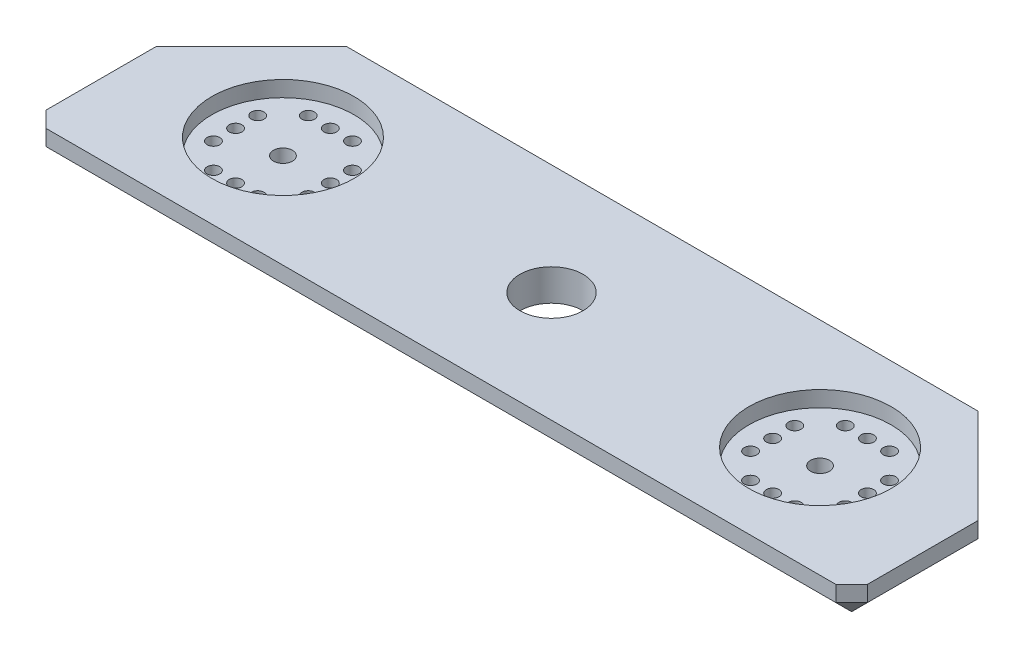
SolidWorks part; units mm, degrees
ref_plane "前视基准面" through (0, 0, 0) normal (0, 0, 1) x (1, 0, 0)
ref_plane "上视基准面" through (0, 0, 0) normal (0, 1, 0) x (1, 0, 0)
ref_plane "右视基准面" through (0, 0, 0) normal (1, 0, 0) x (0, 0, -1)
other "Configuration Table"
sketch "Sketch1" plane through (0, 0, 0) normal (0, 1, 0) x (1, 0, 0)
  line L15 (-65, -17.5) -> (-65, 2.5)
  line L16 (-65, -17.5) -> (65, -17.5)
  line L17 (-65, -17.5) -> (-65, 17.5)
  line L18 (-65, 17.5) -> (65, 17.5)
  line L19 (65, -17.5) -> (65, 17.5)
  line L20 (-65, -17.5) -> (65, 17.5) construction
  line L21 (-65, 17.5) -> (65, -17.5) construction
  line L22 (-65, 2.5) -> (-50, 17.5)
  line L23 (0, 0) -> (0, 17.5) construction
  line L24 (65, 2.5) -> (50, 17.5)
  point P0 (0, 0)
  dimension "D2" = 35
  dimension "D4" = 15
  dimension "D1" = 130
  dimension "D3" = 20
extrude "Boss-Extrude1" add sketch "Sketch1" along normal blind 5
sketch "Sketch2" plane through (0, 5, 0) normal (0, 1, 0) x (1, 0, 0)
  line L0 (0, 0) -> (-42.5, 0) construction
  line L1 (0, 0) -> (0, -17.5) construction
  line L2 (-65, -17.5) -> (65, -17.5) construction
  circle A0 centre (-42.5, 0) radius 11.25
  circle A1 centre (42.5, 0) radius 11.25
  dimension "D1" = 22.5
  dimension "D2" = 42.5
extrude "Cut-Extrude1" cut sketch "Sketch2" against normal blind 2.5
sketch "Sketch3" plane through (0, 5, 0) normal (0, 1, 0) x (1, 0, 0)
  line L0 (0, 0) -> (42.5, 0) construction
  line L1 (42.5, 7.5) -> (46, 7.5) construction
  line L2 (42.5, 7.5) -> (42.5, 13.9618) construction
  line L3 (0, 0) -> (0, 17.5) construction
  line L4 (-50, 17.5) -> (50, 17.5) construction
  line L5 (-42.5, 7.5) -> (-42.5, 13.9618) construction
  line L6 (-42.5, 7.5) -> (-46, 7.5) construction
  circle A0 centre (42.5, 0) radius 1.5
  circle A1 centre (42.5, 0) radius 7.5 construction
  circle A2 centre (42.5, 7.5) radius 1
  circle A3 centre (46, 7.5) radius 1
  circle A4 centre (39, 7.5) radius 1
  circle A5 centre (50, 3.5) radius 1
  circle A6 centre (50, 0) radius 1
  circle A7 centre (50, -3.5) radius 1
  circle A8 centre (46, -7.5) radius 1
  circle A9 centre (42.5, -7.5) radius 1
  circle A10 centre (39, -7.5) radius 1
  circle A11 centre (35, -3.5) radius 1
  circle A12 centre (35, 0) radius 1
  circle A13 centre (35, 3.5) radius 1
  circle A14 centre (-42.5, 0) radius 7.5 construction
  circle A15 centre (-35, 3.5) radius 1
  circle A16 centre (-35, 0) radius 1
  circle A17 centre (-35, -3.5) radius 1
  circle A18 centre (-39, -7.5) radius 1
  circle A19 centre (-42.5, -7.5) radius 1
  circle A20 centre (-46, -7.5) radius 1
  circle A21 centre (-50, -3.5) radius 1
  circle A22 centre (-50, 0) radius 1
  circle A23 centre (-50, 3.5) radius 1
  circle A24 centre (-39, 7.5) radius 1
  circle A25 centre (-46, 7.5) radius 1
  circle A26 centre (-42.5, 7.5) radius 1
  circle A27 centre (-42.5, 0) radius 1.5
  point P37 (42.5, 0)
  point P63 (-42.5, 0)
  dimension "D1" = 2
  dimension "D2" = 15
  dimension "D3" = 3
  dimension "D4" = 2
  dimension "D5" = 3.5
  dimension "D6" = 4
extrude "Cut-Extrude3" cut sketch "Sketch3" against normal blind 12.5
chamfer "Chamfer1" distance 2.5 angle 45 8 edges at (-57.5, 0, -10) (-65, 0, 7.5) (-65, 2.5, 17.5) (0, 0, 17.5) (65, 2.5, 17.5) (0, 0, -17.5) (65, 0, 7.5) (57.5, 0, -10)
sketch "Sketch5" plane through (0, 5, 0) normal (0, 1, 0) x (1, 0, 0)
  circle A0 centre (0, 0) radius 5
  dimension "D1" = 10
extrude "Cut-Extrude4" cut sketch "Sketch5" against normal blind 12.5
